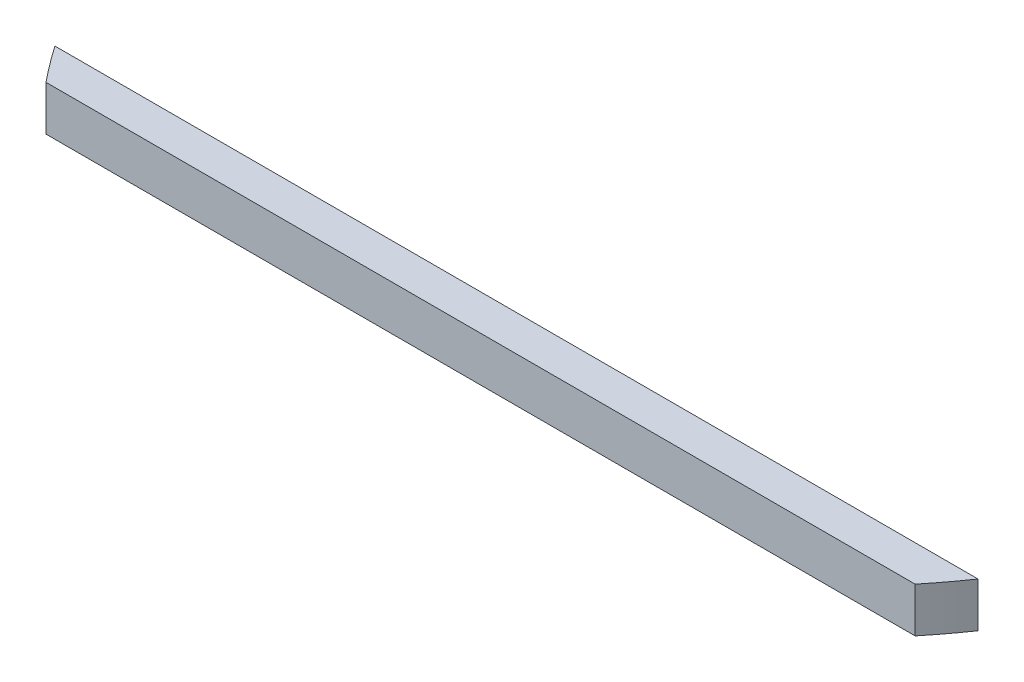
SolidWorks part; units mm, degrees
ref_plane "Front Plane" through (0, 0, 0) normal (0, 0, 1) x (1, 0, 0)
ref_plane "Top Plane" through (0, 0, 0) normal (0, 1, 0) x (1, 0, 0)
ref_plane "Right Plane" through (0, 0, 0) normal (1, 0, 0) x (0, 0, -1)
sketch "Sketch1" plane through (0, 0, 0) normal (0, 1, 0) x (1, 0, 0)
  line L0 (0, 0) -> (0, -37.5) construction
  line L2 (-48.4355, -39.5) -> (48.4355, -39.5)
  line L4 (-51.4393, -35.5) -> (51.4393, -35.5)
  line L6 (-48.5276, -39.3868) -> (51.4393, -35.5) construction
  line L7 (-51.4393, -35.5) -> (48.5276, -39.3868) construction
  arc A0 (-51.4393, -35.5) -> (-48.4355, -39.5) centre (0, 0) ccw
  arc A1 (48.4355, -39.5) -> (51.4393, -35.5) centre (0, 0) ccw
  dimension "D3" = 96.871
  dimension "D1" = 125
  dimension "D2" = 37.5
  dimension "D4" = 102.8786
extrude "Boss-Extrude1" add sketch "Sketch1" along normal blind 5
